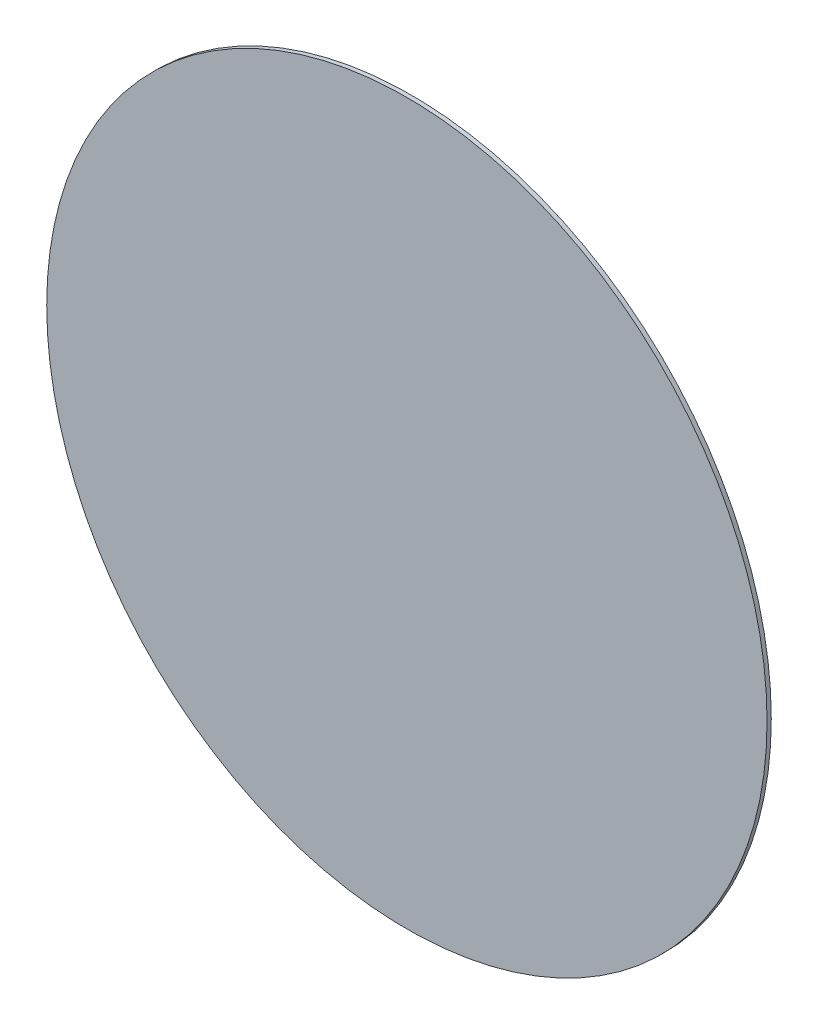
SolidWorks part; units mm, degrees
ref_plane "Front Plane" through (0, 0, 0) normal (0, 0, 1) x (1, 0, 0)
ref_plane "Top Plane" through (0, 0, 0) normal (0, 1, 0) x (1, 0, 0)
ref_plane "Right Plane" through (0, 0, 0) normal (1, 0, 0) x (0, 0, -1)
sketch "Sketch1" plane through (0, 0, 0) normal (0, 0, 1) x (1, 0, 0)
  circle A0 centre (0, 0) radius 256
extrude "Skin" add sketch "Sketch1" along normal blind 3
